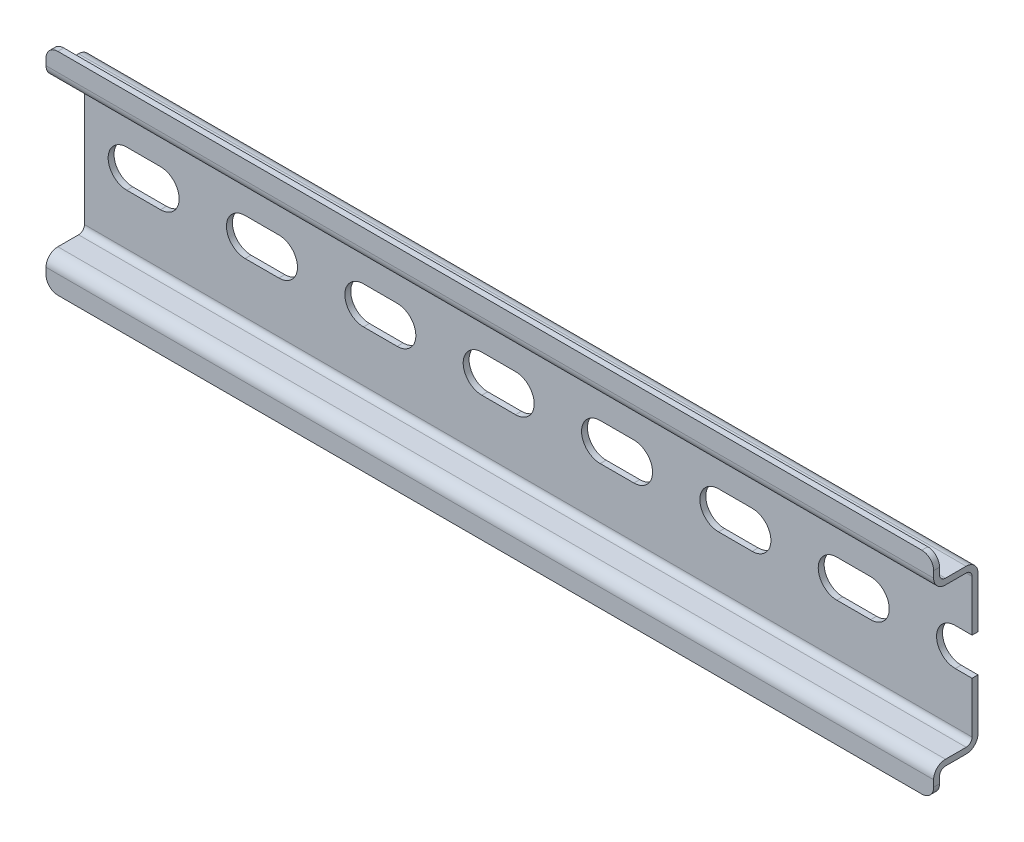
SolidWorks part; units mm, degrees
material "AISI 1045 Steel, cold drawn"
ref_plane "Front" through (0, 0, 0) normal (0, 0, 1) x (1, 0, 0)
ref_plane "Top" through (0, 0, 0) normal (0, 1, 0) x (1, 0, 0)
ref_plane "Right" through (0, 0, 0) normal (1, 0, 0) x (0, 0, -1)
sketch "Sketch1" plane through (0, 0, 0) normal (1, 0, 0) x (0, 0, -1)
  line L0 (0, 0) -> (0, 3.1)
  line L1 (2, 5.1) -> (5.5, 5.1)
  line L2 (6.5, 6.1) -> (6.5, 29.6)
  line L3 (5.5, 30.6) -> (2, 30.6)
  line L4 (0, 32.6) -> (0, 35.7)
  line L5 (6.5, 17.85) -> (-5.5369, 17.85) construction
  line L6 (1, 0) -> (1, 3.1)
  line L7 (2, 4.1) -> (5.5, 4.1)
  line L8 (7.5, 6.1) -> (7.5, 29.6)
  line L9 (5.5, 31.6) -> (2, 31.6)
  line L10 (1, 32.6) -> (1, 35.7)
  line L11 (0, 0) -> (1, 0)
  line L12 (0, 35.7) -> (1, 35.7)
  arc A0 (2, 30.6) -> (0, 32.6) centre (2, 32.6) cw
  arc A1 (0, 3.1) -> (2, 5.1) centre (2, 3.1) cw
  arc A2 (6.5, 29.6) -> (5.5, 30.6) centre (5.5, 29.6) ccw
  arc A3 (5.5, 5.1) -> (6.5, 6.1) centre (5.5, 6.1) ccw
  arc A4 (1, 3.1) -> (2, 4.1) centre (2, 3.1) cw
  arc A5 (5.5, 4.1) -> (7.5, 6.1) centre (5.5, 6.1) ccw
  arc A6 (7.5, 29.6) -> (5.5, 31.6) centre (5.5, 29.6) ccw
  arc A7 (2, 31.6) -> (1, 32.6) centre (2, 32.6) cw
  dimension "D1" = 2
  dimension "D2" = 1
  dimension "D3" = 6.5
  dimension "D4" = 35.7
  dimension "D5" = 25.5
  dimension "D6" = 1
extrude "Boss-Extrude1" add sketch "Sketch1" along normal blind 150
sketch "Sketch2" plane through (0, 0, 0) normal (0, 0, 1) x (1, 0, 0)
  line L0 (0, 17.85) -> (150, 17.85) construction
  line L1 (0, 29.6) -> (0, 6.1) construction
  line L2 (150, 29.6) -> (150, 6.1) construction
  line L3 (7.15, 17.85) -> (12.85, 17.85) construction
  line L4 (7.15, 21) -> (12.85, 21)
  line L5 (7.15, 14.7) -> (12.85, 14.7)
  arc A0 (7.15, 21) -> (7.15, 14.7) centre (7.15, 17.85) ccw
  arc A1 (12.85, 14.7) -> (12.85, 21) centre (12.85, 17.85) ccw
  point P8 (10, 17.85)
  dimension "D1" = 6.3
  dimension "D2" = 5.7
  dimension "D3" = 10
extrude "Cut-Extrude1" cut sketch "Sketch2" against normal through all
pattern_linear "LPattern1" count 8 spacing 20 along (1, 0, 0) of "Cut-Extrude1"
fillet "Fillet1" radius 2 4 edges at (150, 0, -0.5) (150, 35.7, -0.5) (0, 0, -0.5) (0, 35.7, -0.5)
equation "\"Length\"=150"
equation "\"D1@Boss-Extrude1\"=\"Length\""
equation "\"Hole Spacing\"= 20"
equation "\"D3@LPattern1\"=\"Hole Spacing\""
